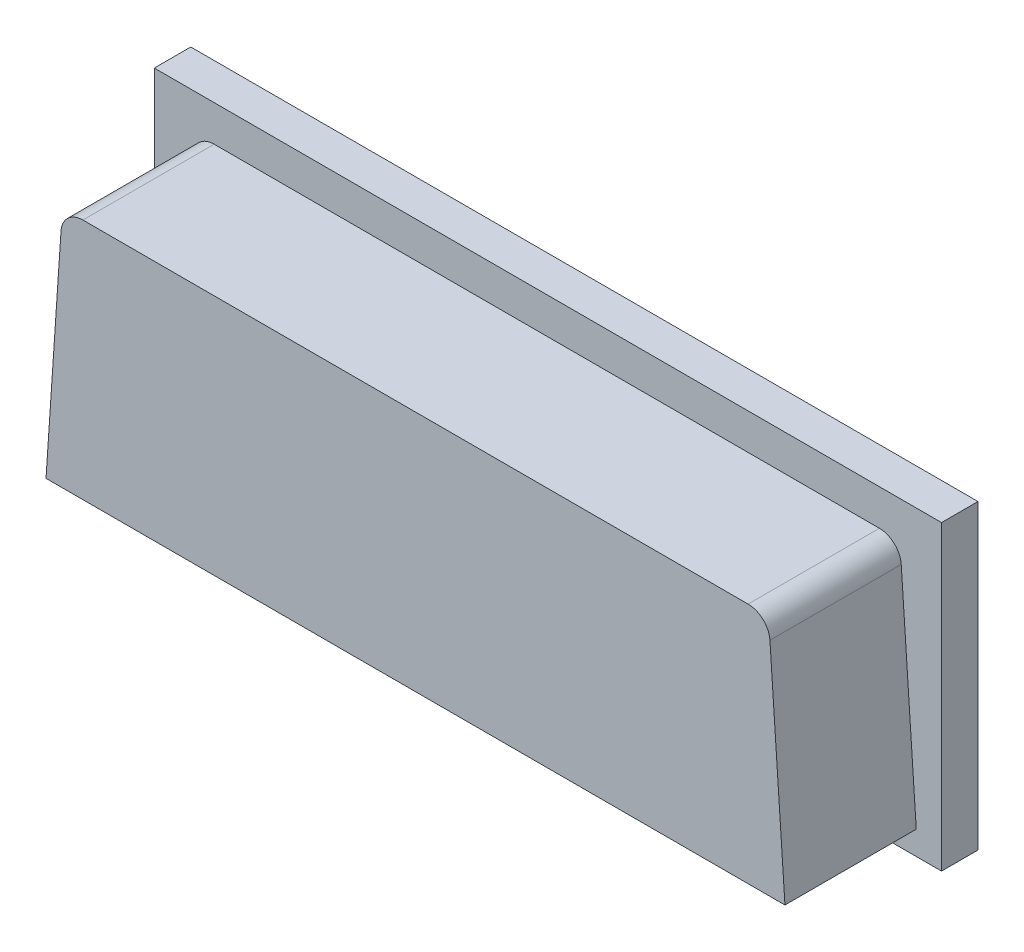
SolidWorks part; units mm, degrees
ref_plane "Přední rovina" through (0, 0, 0) normal (0, 0, 1) x (1, 0, 0)
ref_plane "Horní rovina" through (0, 0, 0) normal (0, 1, 0) x (1, 0, 0)
ref_plane "Pravá rovina" through (0, 0, 0) normal (1, 0, 0) x (0, 0, -1)
sketch "Skica1" plane through (0, 0, 0) normal (0, 0, 1) x (1, 0, 0)
  line L0 (50.65, 33.2) -> (50.65, 0) construction
  line L1 (0, 0) -> (101.3, 0)
  line L2 (0, 0) -> (2.25, 33.2)
  line L3 (2.25, 33.2) -> (99.05, 33.2)
  line L4 (101.3, 0) -> (99.05, 33.2)
  dimension "D1" = 33.2
  dimension "D2" = 96.8
  dimension "D3" = 101.3
extrude "Přidat vysunutím1" add sketch "Skica1" along normal blind 18
fillet "Zaoblit1" radius 3 2 edges at (2.25, 33.2, 9) (99.05, 33.2, 9)
sketch "Skica2" plane through (0, 0, 0) normal (0, 0, -1) x (-1, 0, 0)
  line L0 (-96.2464, 33.2) -> (-5.0536, 33.2) construction
  line L1 (-104.7633, 38.1358) -> (3.1553, 38.1358)
  line L2 (-104.7633, 38.1358) -> (-104.7633, -3.245)
  line L3 (-104.7633, -3.245) -> (3.1553, -3.245)
  line L4 (3.1553, 38.1358) -> (3.1553, -3.245)
  dimension "D1" = 41.3808
  dimension "D2" = 107.9186
extrude "Přidat vysunutím2" add sketch "Skica2" along normal blind 5
sketch "Skica3" plane through (0, 0, 18) normal (0, 0, 1) x (1, 0, 0)
  line L0 (75.65, 42.6879) -> (75.65, -16.3954) construction
  line L1 (104.7633, 38.1358) -> (104.7633, -3.245) construction
  line L2 (25.65, 46.6511) -> (25.65, -13.4611) construction
  line L3 (-3.1553, -3.245) -> (-3.1553, 38.1358) construction
  line L4 (25.65, 16.595) -> (75.65, 16.595) construction
  line L5 (50.65, 16.595) -> (50.65, 34.0043) construction
  line L6 (50.65, 16.595) -> (50.65, -0.4476) construction
  line L9 (96.2464, 33.2) -> (5.0536, 33.2) construction
  circle A0 centre (55.945, 11.3) radius 2.35
  circle A1 centre (45.355, 11.3) radius 2.35
  circle A2 centre (55.945, 21.89) radius 2.35
  circle A3 centre (45.355, 21.89) radius 2.35
  point P17 (55.1811, 11.7476)
  dimension "D3" = 4.7
  dimension "D1" = 25.65
  dimension "D2" = 25.65
  dimension "D4" = 10.59
  dimension "D5" = 10.59
  dimension "D6" = 11.31
  dimension "D7" = 19.705
